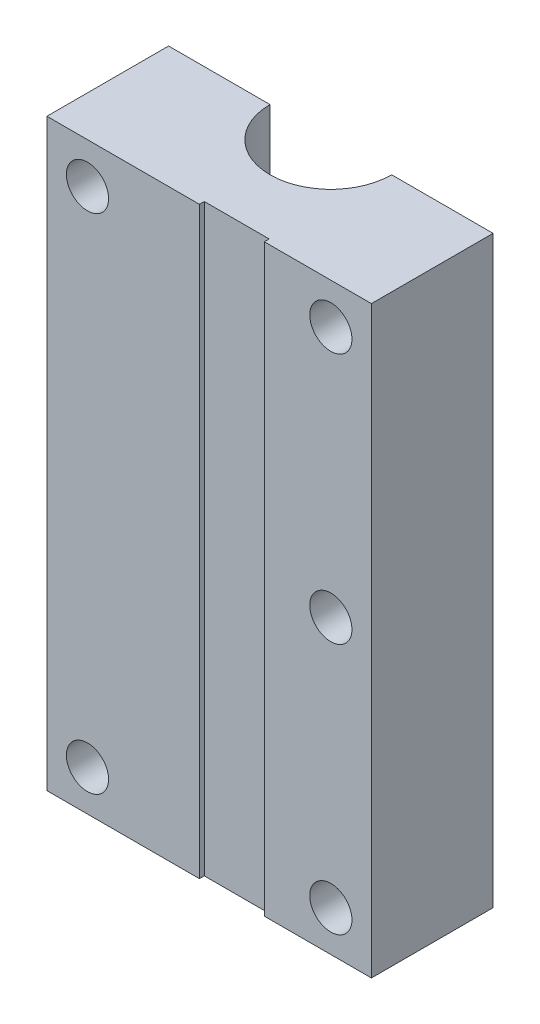
SolidWorks part; units mm, degrees
ref_plane "Front Plane" through (0, 0, 0) normal (0, 0, 1) x (1, 0, 0)
ref_plane "Top Plane" through (0, 0, 0) normal (0, 1, 0) x (1, 0, 0)
ref_plane "Right Plane" through (0, 0, 0) normal (1, 0, 0) x (0, 0, -1)
sketch "Sketch1" plane through (0, 0, 0) normal (0, 1, 0) x (1, 0, 0)
  line L0 (27.5, 15) -> (40, 15)
  line L1 (0, 0) -> (40, 0)
  line L2 (0, 0) -> (0, 15)
  line L3 (0, 15) -> (12.5, 15)
  line L4 (40, 0) -> (40, 15)
  arc A0 (12.5, 15) -> (27.5, 15) centre (20, 15) ccw
  dimension "D3" = 15
  dimension "D1" = 40
  dimension "D2" = 15
  dimension "D4" = 20
  dimension "D5" = 0
extrude "Boss-Extrude1" add sketch "Sketch1" along normal mid plane 72
sketch "Sketch2" plane through (0, 0, 0) normal (0, 1, 0) x (1, 0, 0)
  line L0 (12.5, 15) -> (0, 15) construction
  line L1 (8.4589, 15) -> (31.4589, 15)
  arc A0 (8.4589, 15) -> (31.4589, 15) centre (19.9589, 15) ccw
  dimension "D1" = 23
  dimension "D2" = 0
extrude "Cut-Extrude1" cut sketch "Sketch2" against normal mid plane 33
sketch "Sketch3" plane through (0, 0, 0) normal (0, 0, 1) x (1, 0, 0)
  line L0 (0, 36) -> (0, -36) construction
  line L1 (18.8, 38.3259) -> (26.8, 38.3259)
  line L2 (18.8, 38.3259) -> (18.8, -38.8056)
  line L3 (18.8, -38.8056) -> (26.8, -38.8056)
  line L4 (26.8, 38.3259) -> (26.8, -38.8056)
  dimension "D1" = 18.8
  dimension "D2" = 8
extrude "Cut-Extrude2" cut sketch "Sketch3" against normal blind 0.6
sketch "Sketch4" plane through (0, 0, 0) normal (0, 0, 1) x (1, 0, 0)
  line L0 (0, 36) -> (18.8, 36) construction
  line L1 (0, 36) -> (0, -36) construction
  line L2 (26.8, 36) -> (40, 36) construction
  line L3 (40, 36) -> (40, -36) construction
  line L4 (0, -36) -> (18.8, -36) construction
  line L5 (26.8, -36) -> (40, -36) construction
  circle A0 centre (5, 31) radius 2.6
  circle A1 centre (35, 31) radius 2.6
  circle A2 centre (35, -31) radius 2.6
  circle A3 centre (5, -31) radius 2.6
  circle A4 centre (35, 0) radius 2.6
  dimension "D1" = 5.2
  dimension "D2" = 5.2
  dimension "D3" = 5.2
  dimension "D4" = 5.2
  dimension "D13" = 5.2
  dimension "D5" = 5
  dimension "D6" = 5
  dimension "D7" = 5
  dimension "D8" = 5
  dimension "D9" = 5
  dimension "D10" = 5
  dimension "D11" = 5
  dimension "D12" = 5
  dimension "D14" = 5
  dimension "D15" = 0
extrude "Cut-Extrude3" cut sketch "Sketch4" against normal through all
equation "\"D4@Sketch1\"=\"D1@Sketch1\"/2"
equation "\"D2@Sketch4\"=\"D1@Sketch4\""
equation "\"D3@Sketch4\"=\"D1@Sketch4\""
equation "\"D4@Sketch4\"=\"D1@Sketch4\""
equation "\"D6@Sketch4\"=\"D5@Sketch4\""
equation "\"D7@Sketch4\"=\"D5@Sketch4\""
equation "\"D8@Sketch4\"=\"D5@Sketch4\""
equation "\"D9@Sketch4\"=\"D5@Sketch4\""
equation "\"D10@Sketch4\"=\"D5@Sketch4\""
equation "\"D11@Sketch4\"=\"D5@Sketch4\""
equation "\"D12@Sketch4\"=\"D5@Sketch4\""
equation "\"D13@Sketch4\"=\"D1@Sketch4\""
equation "\"D14@Sketch4\"=\"D5@Sketch4\""
